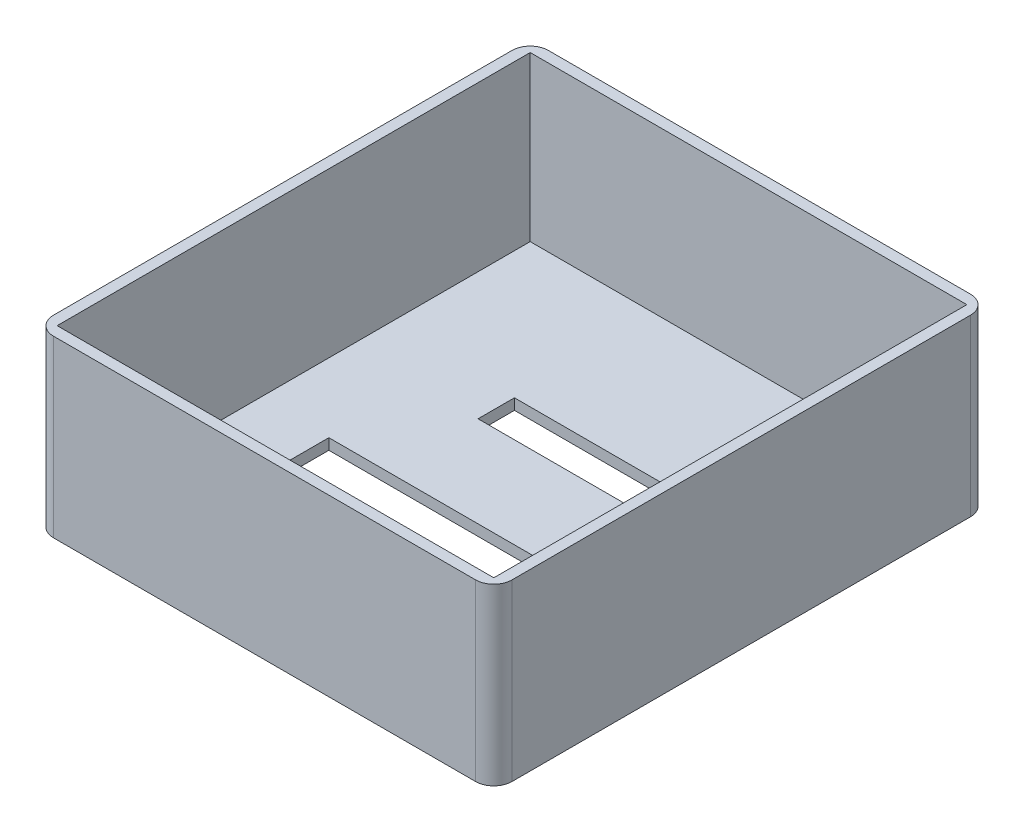
SolidWorks part; units mm, degrees
ref_plane "Front Plane" through (0, 0, 0) normal (0, 0, 1) x (1, 0, 0)
ref_plane "Top Plane" through (0, 0, 0) normal (0, 1, 0) x (1, 0, 0)
ref_plane "Right Plane" through (0, 0, 0) normal (1, 0, 0) x (0, 0, -1)
sketch "Sketch1" plane through (0, 0, 0) normal (0, 1, 0) x (1, 0, 0)
  line L1 (-63, 68) -> (63, 68)
  line L2 (-63, 68) -> (-63, -68)
  line L3 (-63, -68) -> (63, -68)
  line L4 (63, 68) -> (63, -68)
  line L5 (-63, 68) -> (63, -68) construction
  line L6 (-63, -68) -> (63, 68) construction
  point P0 (0, 0)
  dimension "D1" = 136
  dimension "D2" = 126
extrude "Boss-Extrude1" add sketch "Sketch1" along normal blind 3
sketch "Sketch2" plane through (0, 3, 0) normal (0, 1, 0) x (1, 0, 0)
  line L1 (-63, 68) -> (63, 68)
  line L2 (-63, 68) -> (-63, -68)
  line L3 (-63, -68) -> (63, -68)
  line L4 (63, 68) -> (63, -68)
  line L5 (-60, 65) -> (60, 65)
  line L6 (-60, 65) -> (-60, -65)
  line L7 (-60, -65) -> (60, -65)
  line L8 (60, 65) -> (60, -65)
  line L9 (-60, 65) -> (60, -65) construction
  line L10 (-60, -65) -> (60, 65) construction
  point P6 (0, 0)
  dimension "D1" = 3
  dimension "D2" = 3
extrude "Boss-Extrude2" add sketch "Sketch2" along normal blind 45
fillet "Fillet1" radius 5 4 edges at (-63, 24, -68) (63, 24, -68) (63, 24, 68) (-63, 24, 68)
sketch "Sketch4" plane through (0, 3, 0) normal (0, 1, 0) x (1, 0, 0)
  line L1 (41, -32.3285) -> (-41, -32.3285)
  line L2 (41, -32.3285) -> (41, -9.3285)
  line L3 (41, -9.3285) -> (-41, -9.3285)
  line L4 (-41, -32.3285) -> (-41, -9.3285)
  line L5 (41, -32.3285) -> (-41, -9.3285) construction
  line L6 (41, -9.3285) -> (-41, -32.3285) construction
  line L7 (25, 15.6715) -> (-25, 15.6715)
  line L8 (25, 15.6715) -> (25, 25.6715)
  line L9 (25, 25.6715) -> (-25, 25.6715)
  line L10 (-25, 15.6715) -> (-25, 25.6715)
  line L11 (25, 15.6715) -> (-25, 25.6715) construction
  line L12 (25, 25.6715) -> (-25, 15.6715) construction
  point P0 (0, -20.8285)
  point P5 (0, 0)
  point P9 (0, 20.6715)
  point P14 (0, 0)
  point P15 (0, -20.8285)
  dimension "D1" = 23
  dimension "D2" = 82
  dimension "D3" = 25
  dimension "D4" = 10
  dimension "D5" = 50
extrude "Cut-Extrude1" cut sketch "Sketch4" against normal blind 10
